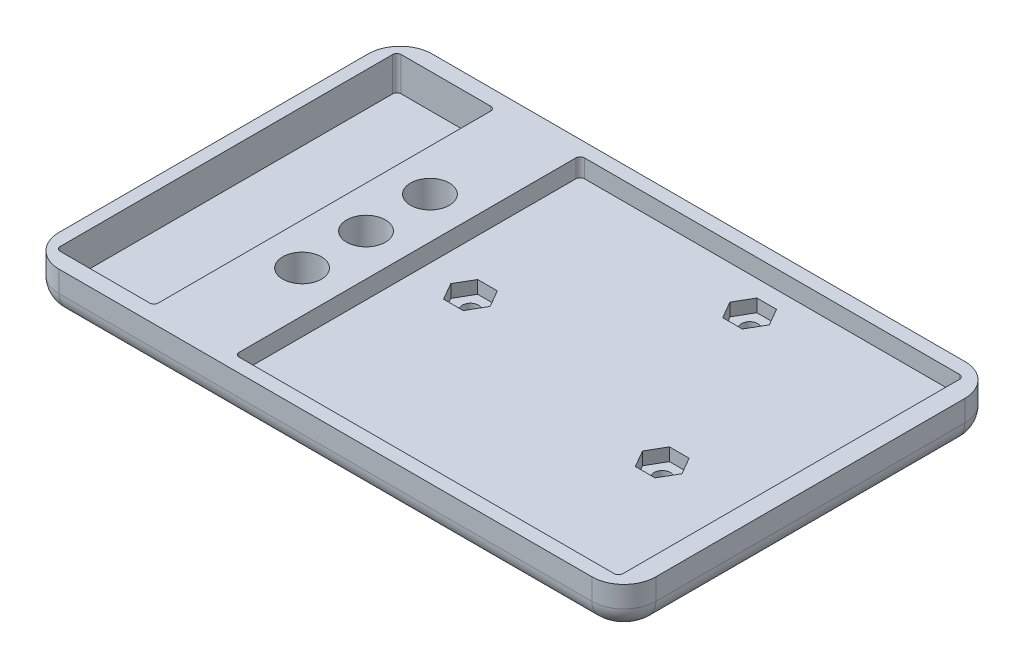
SolidWorks part; units mm, degrees
ref_plane "Front Plane" through (0, 0, 0) normal (0, 0, 1) x (1, 0, 0)
ref_plane "Top Plane" through (0, 0, 0) normal (0, 1, 0) x (1, 0, 0)
ref_plane "Right Plane" through (0, 0, 0) normal (1, 0, 0) x (0, 0, -1)
sketch "Sketch1" plane through (0, 0, 0) normal (0, 1, 0) x (1, 0, 0)
  line L1 (0, 0) -> (140, 0)
  line L2 (0, 0) -> (0, 87.5)
  line L3 (0, 87.5) -> (140, 87.5)
  line L4 (140, 0) -> (140, 87.5)
  dimension "D1" = 87.5
  dimension "D2" = 140
extrude "Boss-Extrude1" add sketch "Sketch1" along normal blind 10
sketch "Sketch2" plane through (0, 10, 0) normal (0, 1, 0) x (1, 0, 0)
  line L5 (140, 43.75) -> (135.5, 43.75) construction
  line L7 (45.5, 84.25) -> (135.5, 84.25)
  line L9 (45.5, 84.25) -> (45.5, 3.25)
  line L10 (45.5, 3.25) -> (135.5, 3.25)
  line L11 (135.5, 84.25) -> (135.5, 3.25)
  line L12 (140, 0) -> (140, 87.5) construction
  line L13 (90.5, 84.25) -> (90.5, 87.5) construction
  line L14 (140, 87.5) -> (0, 87.5) construction
  line L15 (90.5, 3.25) -> (90.5, 0) construction
  line L16 (0, 0) -> (140, 0) construction
  dimension "D3" = 81
  dimension "D1" = 4.5
  dimension "D2" = 90
extrude "Cut-Extrude1" cut sketch "Sketch2" against normal blind 4.25
sketch "Sketch5" plane through (0, 10, 0) normal (0, 1, 0) x (1, 0, 0)
  line L0 (0, 87.5) -> (0, 0) construction
  line L1 (3, 3.75) -> (26, 3.75)
  line L2 (3, 3.75) -> (3, 83.75)
  line L3 (3, 83.75) -> (26, 83.75)
  line L4 (26, 3.75) -> (26, 83.75)
  line L5 (14.5, 83.75) -> (14.5, 87.5) construction
  line L6 (140, 87.5) -> (0, 87.5) construction
  line L7 (14.5, 3.75) -> (14.5, 0) construction
  line L8 (0, 0) -> (140, 0) construction
  dimension "D1" = 23
  dimension "D2" = 80
  dimension "D3" = 3
extrude "Cut-Extrude2" cut sketch "Sketch5" against normal blind 8
sketch "Sketch11" plane through (0, 5.75, 0) normal (0, 1, 0) x (1, 0, 0)
  line L0 (90.5, 84.25) -> (90.5, 3.25) construction
  line L1 (135.5, 84.25) -> (45.5, 84.25) construction
  line L2 (45.5, 3.25) -> (135.5, 3.25) construction
  line L3 (45.5, 43.75) -> (135.5, 43.75) construction
  line L4 (45.5, 84.25) -> (45.5, 3.25) construction
  line L5 (135.5, 3.25) -> (135.5, 84.25) construction
  line L7 (90.5, 43.75) -> (56.75, 43.75) construction
  line L8 (90.5, 43.75) -> (90.5, 47.25) construction
  line L9 (90.5, 47.25) -> (56.75, 47.25) construction
  line L10 (56.75, 43.75) -> (56.75, 47.25) construction
  line L15 (90.5, 43.75) -> (113.25, 43.75) construction
  line L16 (90.5, 43.75) -> (90.5, 35.75) construction
  line L17 (90.5, 35.75) -> (113.25, 35.75) construction
  line L18 (113.25, 43.75) -> (113.25, 35.75) construction
  line L19 (90.5, 43.75) -> (93.25, 43.75) construction
  line L20 (90.5, 43.75) -> (90.5, 76.25) construction
  line L21 (90.5, 76.25) -> (93.25, 76.25) construction
  line L22 (93.25, 43.75) -> (93.25, 76.25) construction
  dimension "D1" = 3.5
  dimension "D2" = 33.75
  dimension "D3" = 32.5
  dimension "D4" = 2.75
  dimension "D5" = 8
  dimension "D6" = 22.75
hole_wizard "#6 Clearance Hole1" positions "Sketch17" profile "Sketch18" hole size "#6" standard "ANSI Inch" end condition through all
sketch "Sketch17" plane through (0, 5.75, 0) normal (0, 1, 0) x (1, 0, 0)
  point P0 (56.75, 47.25)
  point P3 (93.25, 76.25)
  point P6 (113.25, 35.75)
sketch "Sketch18" plane through (56.75, 5.75, -47.25) normal (1, 0, 0) x (0, 0, 1)
  line L0 (0, 0) -> (0, 5.75)
  line L1 (0, 5.75) -> (1.8986, 5.75)
  line L2 (1.8986, 5.75) -> (1.8986, 0)
  line L5 (1.8986, 0) -> (0, 0)
  line L11 (0, -6.35) -> (0, 107.95) construction
  dimension "Thru Hole Dia." = 3.7973
  dimension "Thru Hole Depth" = 5.75
sketch "Sketch19" plane through (0, 5.75, 0) normal (0, 1, 0) x (1, 0, 0)
  line L0 (135.5, 84.25) -> (45.5, 84.25) construction
  line L1 (59.0594, 51.25) -> (54.4406, 51.25)
  line L2 (54.4406, 51.25) -> (52.1312, 47.25)
  line L3 (52.1312, 47.25) -> (54.4406, 43.25)
  line L4 (54.4406, 43.25) -> (59.0594, 43.25)
  line L5 (59.0594, 43.25) -> (61.3688, 47.25)
  line L6 (61.3688, 47.25) -> (59.0594, 51.25)
  line L7 (97.8688, 76.25) -> (95.5594, 80.25)
  line L8 (95.5594, 80.25) -> (90.9406, 80.25)
  line L9 (90.9406, 80.25) -> (88.6312, 76.25)
  line L10 (88.6312, 76.25) -> (90.9406, 72.25)
  line L11 (90.9406, 72.25) -> (95.5594, 72.25)
  line L12 (95.5594, 72.25) -> (97.8688, 76.25)
  line L13 (117.8688, 35.75) -> (115.5594, 39.75)
  line L14 (115.5594, 39.75) -> (110.9406, 39.75)
  line L15 (110.9406, 39.75) -> (108.6312, 35.75)
  line L16 (108.6312, 35.75) -> (110.9406, 31.75)
  line L17 (110.9406, 31.75) -> (115.5594, 31.75)
  line L18 (115.5594, 31.75) -> (117.8688, 35.75)
  line L19 (135.5, 84.25) -> (45.5, 84.25) construction
  circle A0 centre (56.75, 47.25) radius 4 construction
  circle A1 centre (93.25, 76.25) radius 4 construction
  circle A2 centre (113.25, 35.75) radius 4 construction
  dimension "D1" = 8
extrude "Cut-Extrude4" cut sketch "Sketch19" against normal blind 3
fillet "Fillet1" radius 7.5 4 edges at (0, 5, 0) (0, 5, -87.5) (140, 5, -87.5) (140, 5, 0)
sketch "Sketch15" plane through (0, 10, 0) normal (0, 1, 0) x (1, 0, 0)
  line L0 (26, 43.75) -> (45.5, 43.75) construction
  line L9 (26, 3.75) -> (26, 83.75) construction
  line L10 (45.5, 3.25) -> (45.5, 84.25) construction
  line L12 (35.75, 43.75) -> (35.75, 58.75) construction
  line L14 (35.75, 43.75) -> (35.75, 28.75) construction
  line L15 (132.5, 87.5) -> (7.5, 87.5) construction
  line L17 (7.5, 0) -> (132.5, 0) construction
  line L26 (70, 87.5) -> (70, 0) construction
  circle A4 centre (35.75, 43.75) radius 4.55
  circle A5 centre (35.75, 58.75) radius 4.55
  circle A6 centre (35.75, 28.75) radius 4.55
  dimension "D2" = 9.1
  dimension "D1" = 15
extrude "Cut-Extrude3" cut sketch "Sketch15" against normal blind 7.5
fillet "Fillet2" radius 1 8 edges at (3, 6, -3.75) (26, 6, -3.75) (26, 6, -83.75) (3, 6, -83.75) (135.5, 7.875, -3.25) (45.5, 7.875, -3.25) (135.5, 7.875, -84.25) (45.5, 7.875, -84.25)
fillet "Fillet3" radius 5 8 edges at (137.8033, 0, -2.1967) (140, 0, -43.75) (137.8033, 0, -85.3033) (70, 0, -87.5) (2.1967, 0, -85.3033) (0, 0, -43.75) (2.1967, 0, -2.1967) (70, 0, 0)
